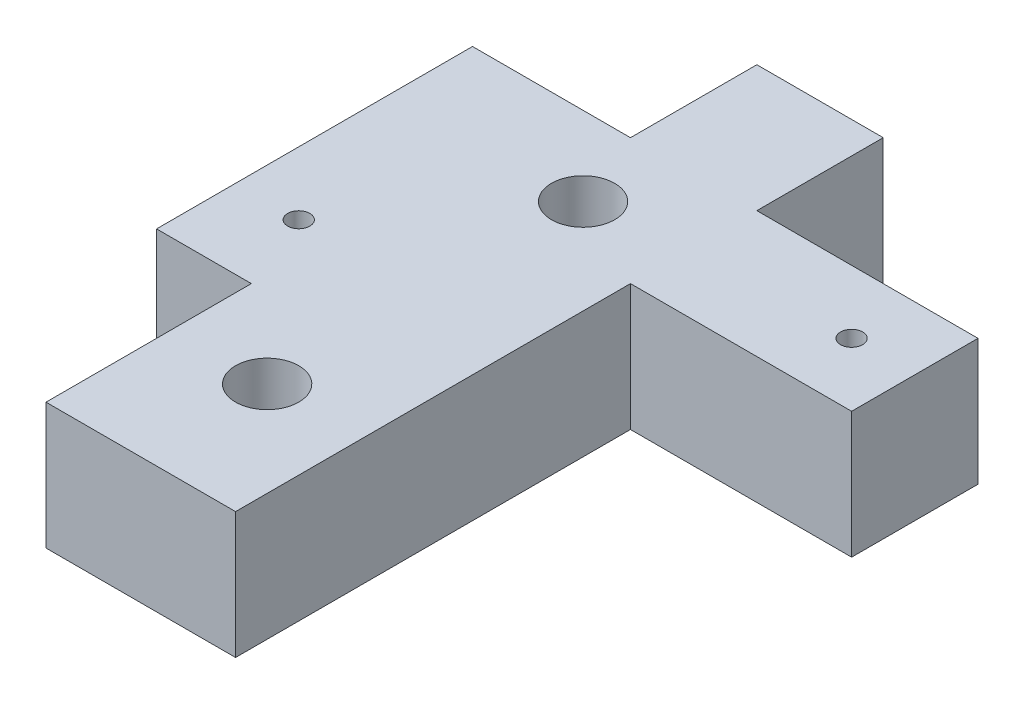
SolidWorks part; units mm, degrees
ref_plane "前视基准面" through (0, 0, 0) normal (0, 0, 1) x (1, 0, 0)
ref_plane "上视基准面" through (0, 0, 0) normal (0, 1, 0) x (1, 0, 0)
ref_plane "右视基准面" through (0, 0, 0) normal (1, 0, 0) x (0, 0, -1)
other "Configuration Table"
sketch "草图1" plane through (0, 0, 0) normal (0, 1, 0) x (1, 0, 0)
  line L1 (0, 0) -> (16, 0)
  line L2 (0, 0) -> (0, -23)
  line L3 (0, -23) -> (16, -23)
  line L4 (16, 0) -> (16, -23)
  circle A3 centre (14, -6) radius 0.35
  circle A5 centre (2, -11.5) radius 0.35
  dimension "D3" = 6
  dimension "D6" = 11.5
  dimension "D7" = 0.7
  dimension "D1" = 23
  dimension "D2" = 16
  dimension "D4" = 2
  dimension "D5" = 2
extrude "凸台-拉伸1" add sketch "草图1" along normal blind 4
sketch "草图2" plane through (0, 0, 0) normal (0, -1, 0) x (1, 0, 0)
  line L0 (6, 23) -> (6, 16.5)
  line L2 (6, 6.5) -> (6, 0)
  circle A0 centre (6, 16.5) radius 1
  circle A1 centre (6, 6.5) radius 1
  dimension "D1" = 2
  dimension "D2" = 10
  dimension "D3" = 6
extrude "切除-拉伸1" cut sketch "草图2" against normal through all contours A0 | A1
sketch "草图3" plane through (0, 0, 0) normal (0, -1, 0) x (1, 0, 0)
  circle A0 centre (6, 16.5) radius 1.5
  circle A1 centre (6, 6.5) radius 1.5
  circle A2 centre (6, 6.5) radius 1 construction
  circle A3 centre (6, 16.5) radius 1 construction
  dimension "D1" = 3
extrude "切除-拉伸2" cut sketch "草图3" against normal blind 2 contours A0 | A1
sketch "草图4" plane through (0, 0, 0) normal (0, -1, 0) x (1, 0, 0)
  line L0 (0, 0) -> (0, 23) construction
  line L1 (0, 23) -> (3, 23)
  line L2 (0, 23) -> (0, 14)
  line L3 (0, 14) -> (3, 14)
  line L4 (3, 23) -> (3, 14)
  line L5 (16, 23) -> (9, 23)
  line L6 (16, 23) -> (16, 8)
  line L7 (16, 8) -> (9, 8)
  line L8 (9, 23) -> (9, 8)
  line L9 (0, 4) -> (5, 4)
  line L10 (0, 4) -> (0, 0)
  line L11 (0, 0) -> (5, 0)
  line L12 (5, 4) -> (5, 0)
  line L13 (0, 0) -> (16, 0) construction
  line L14 (16, 0) -> (16, 23) construction
  line L15 (16, 4) -> (9, 4)
  line L16 (16, 4) -> (16, 0)
  line L17 (16, 0) -> (9, 0)
  line L18 (9, 4) -> (9, 0)
  line L20 (3, 23) -> (9, 23)
  line L21 (3, 23) -> (3, 20.5)
  line L22 (3, 20.5) -> (9, 20.5)
  line L23 (9, 23) -> (9, 20.5)
  circle A0 centre (6, 16.5) radius 1.5 construction
  line M11 (0, 0) -> (16, 0)
  line M12 (16, 0) -> (16, 23)
  line M13 (16, 23) -> (0, 23)
  line M14 (0, 23) -> (0, 0)
  dimension "D9" = 4
  dimension "D1" = 5
  dimension "D2" = 4
  dimension "D3" = 7
  dimension "D4" = 4
  dimension "D5" = 9
  dimension "D6" = 15
  dimension "D7" = 3
  dimension "D8" = 7
extrude "切除-拉伸3" cut sketch "草图4" against normal through all contours L4 L22 L8 M13 | L4 L3 M13 M14 | L8 L7 M13 M12 | L15 L18 M11 M12 | L12 L9 M14 M11
